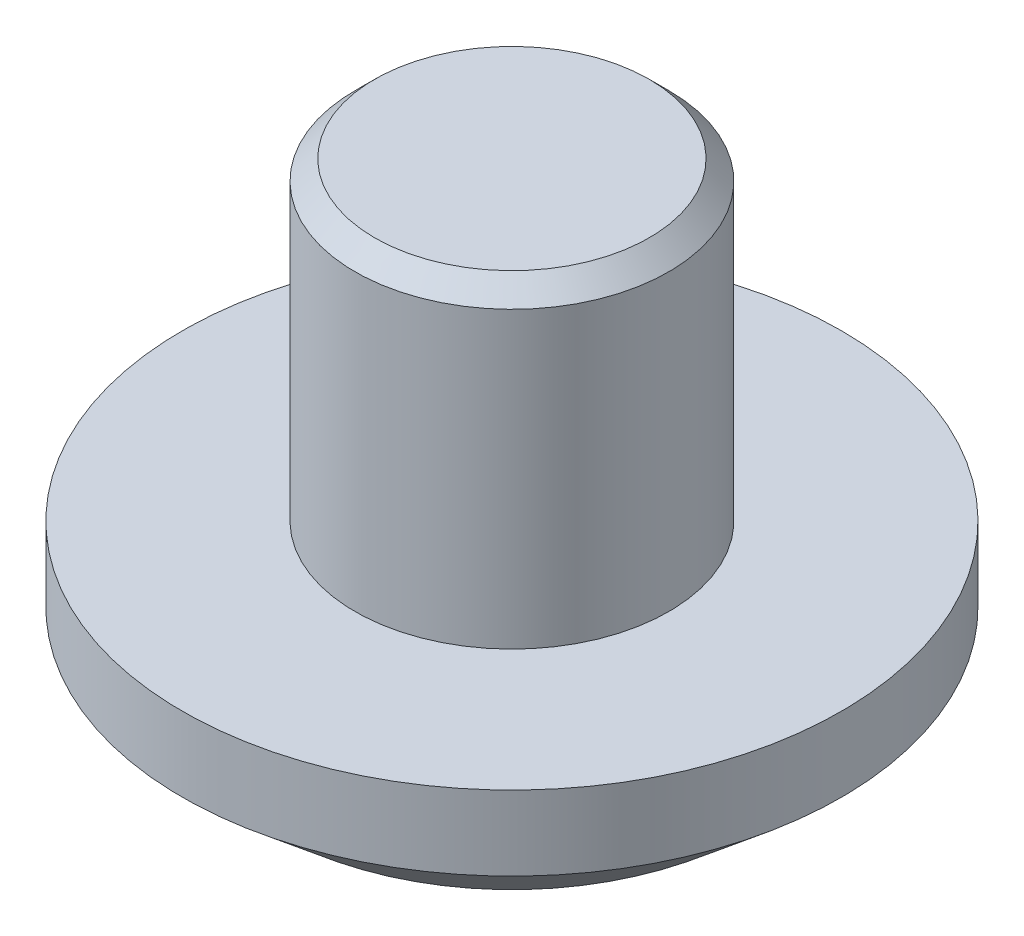
SolidWorks part; units mm, degrees
material "AISI 304"
ref_plane "前视基准面" through (0, 0, 0) normal (0, 0, 1) x (1, 0, 0)
ref_plane "上视基准面" through (0, 0, 0) normal (0, 1, 0) x (1, 0, 0)
ref_plane "右视基准面" through (0, 0, 0) normal (1, 0, 0) x (0, 0, -1)
other "Configuration Table"
sketch "草图1" plane through (0, 0, 0) normal (0, 0, 1) x (1, 0, 0)
  line L0 (0, -1003.6) -> (0, -1.8) construction
  line L1 (2, 0) -> (2, 3.75)
  line L2 (2, 3.75) -> (1.75, 4)
  line L3 (1.75, 4) -> (0, 4)
  line L4 (0, 4) -> (0, 0)
  line L5 (1.25, -1.9) -> (3.0678, -1.9)
  line L6 (3.0678, -1.9) -> (4.2, -0.95)
  line L7 (4.2, -0.95) -> (4.2, 0)
  line L8 (4.2, 0) -> (2, 0)
  line L9 (0, 0) -> (1.25, -0.7511)
  line L10 (1.25, -0.7511) -> (1.25, -1.9)
  line L11 (0, 0) -> (0, 4006.9635) construction
  dimension "M" = 4
  dimension "d" = 3.5
  dimension "L" = 4
  dimension "D1" = 45
  dimension "Dk" = 8.4
  dimension "k" = 1.9
  dimension "alpha" = 50
  dimension "D2" = 0.95
  dimension "theta" = 59
  dimension "D3" = 2.5
revolve "旋转1" add sketch "草图1" angle 360 about L11
sketch "草图2" plane through (0, -1.9, 0) normal (0, -1, 0) x (1, 0, 0)
  line L1 (1.4434, 0) -> (0.7217, 1.25)
  line L2 (0.7217, 1.25) -> (-0.7217, 1.25)
  line L3 (-0.7217, 1.25) -> (-1.4434, 0)
  line L4 (-1.4434, 0) -> (-0.7217, -1.25)
  line L5 (-0.7217, -1.25) -> (0.7217, -1.25)
  line L6 (0.7217, -1.25) -> (1.4434, 0)
  circle A0 centre (0, 0) radius 1.25 construction
  circle A1 centre (0, 0) radius 1.25 construction
extrude "切除-拉伸1" cut sketch "草图2" against normal up to surface (1.0327 mm away)
equation "\"D2@草图1\"= 0.5 * \"k@草图1\""
